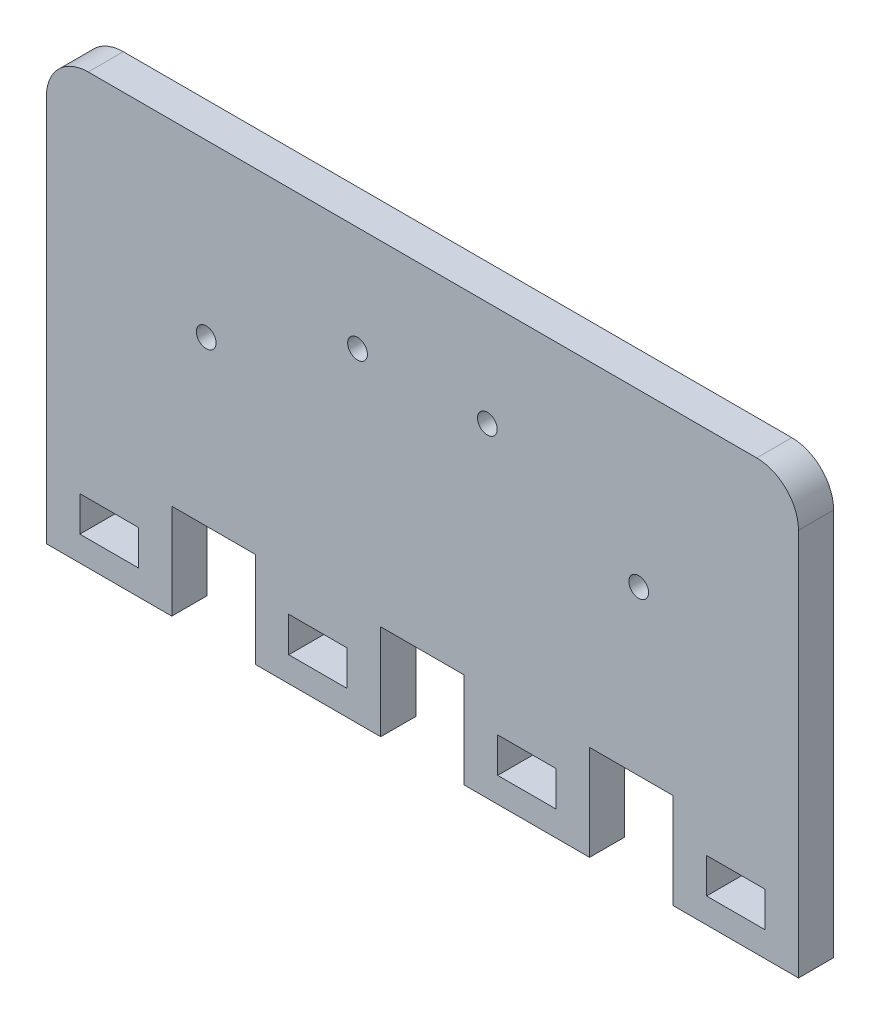
SolidWorks part; units mm, degrees
material "Teak"
ref_plane "Front Plane" through (0, 0, 0) normal (0, 0, 1) x (1, 0, 0)
ref_plane "Top Plane" through (0, 0, 0) normal (0, 1, 0) x (1, 0, 0)
ref_plane "Right Plane" through (0, 0, 0) normal (1, 0, 0) x (0, 0, -1)
sketch "Sketch1" plane through (0, 0, 0) normal (0, 0, 1) x (1, 0, 0)
  line L1 (-30.5325, 25.3111) -> (83.7675, 25.3111)
  line L2 (-30.5325, 25.3111) -> (-30.5325, -30.8229)
  line L3 (-30.5325, -30.8229) -> (83.7675, -30.8229)
  line L4 (83.7675, 25.3111) -> (83.7675, -30.8229)
  dimension "D1" = 56.134
  dimension "D2" = 114.3
extrude "Boss-Extrude1" add sketch "Sketch1" along normal blind 5.334 contours L1 L4 L3 L2
sketch "Sketch2" plane through (0, 0, 5.334) normal (0, 0, 1) x (1, 0, 0)
  line L0 (-30.5325, -30.8229) -> (83.7675, -30.8229) construction
  line L1 (-11.4825, -30.8229) -> (1.2175, -30.8229)
  line L2 (-11.4825, -30.8229) -> (-11.4825, -25.4889)
  line L3 (-11.4825, -25.4889) -> (1.2175, -25.4889)
  line L4 (1.2175, -30.8229) -> (1.2175, -25.4889)
  line L5 (-11.4825, -25.4889) -> (-30.5325, -25.4889) construction
  line L6 (20.2675, -30.8229) -> (32.9675, -30.8229)
  line L7 (20.2675, -30.8229) -> (20.2675, -25.4889)
  line L8 (20.2675, -25.4889) -> (32.9675, -25.4889)
  line L9 (32.9675, -30.8229) -> (32.9675, -25.4889)
  line L10 (52.0175, -30.8229) -> (64.7175, -30.8229)
  line L11 (52.0175, -30.8229) -> (52.0175, -25.4889)
  line L12 (52.0175, -25.4889) -> (64.7175, -25.4889)
  line L13 (64.7175, -30.8229) -> (64.7175, -25.4889)
  line L14 (-30.5325, 25.3111) -> (-30.5325, -30.8229) construction
  line L15 (1.2175, -25.4889) -> (20.2675, -25.4889) construction
  line L16 (32.9675, -25.4889) -> (52.0175, -25.4889) construction
  line L17 (64.7175, -25.4889) -> (83.7675, -25.4889) construction
  line L18 (83.7675, 25.3111) -> (83.7675, -30.8229) construction
  dimension "D1" = 19.05
  dimension "D2" = 12.7
  dimension "D3" = 19.05
  dimension "D4" = 12.7
  dimension "D5" = 19.05
  dimension "D6" = 12.7
  dimension "D7" = 19.05
  dimension "D8" = 5.334
extrude "Cut-Extrude1" cut sketch "Sketch2" against normal through all
fillet "Fillet1" radius 6.35 2 edges at (83.7675, 25.3111, 2.667) (-30.5325, 25.3111, 2.667)
sketch "Sketch3" plane through (0, 0, 0) normal (0, 0, -1) x (-1, 0, 0)
  line L16 (24.1825, 25.3111) -> (-77.4175, 25.3111)
  line L17 (-83.7675, 18.9611) -> (-83.7675, -30.8229)
  line L18 (-83.7675, -30.8229) -> (-64.7175, -30.8229)
  line L19 (-64.7175, -30.8229) -> (-64.7175, -25.4889)
  line L20 (-64.7175, -25.4889) -> (-52.0175, -25.4889)
  line L21 (-52.0175, -25.4889) -> (-52.0175, -30.8229)
  line L22 (-52.0175, -30.8229) -> (-32.9675, -30.8229)
  line L23 (-32.9675, -30.8229) -> (-32.9675, -25.4889)
  line L24 (-32.9675, -25.4889) -> (-20.2675, -25.4889)
  line L25 (-20.2675, -25.4889) -> (-20.2675, -30.8229)
  line L26 (-20.2675, -30.8229) -> (-1.2175, -30.8229)
  line L27 (-1.2175, -30.8229) -> (-1.2175, -25.4889)
  line L28 (-1.2175, -25.4889) -> (11.4825, -25.4889)
  line L29 (11.4825, -25.4889) -> (11.4825, -30.8229)
  line L30 (11.4825, -30.8229) -> (30.5325, -30.8229)
  line L31 (30.5325, -30.8229) -> (30.5325, 18.9611)
  line L32 (24.1825, 25.3111) -> (-77.4175, 25.3111)
  line L33 (-83.7675, 18.9611) -> (-83.7675, -30.8229)
  line L34 (-83.7675, -30.8229) -> (-64.7175, -30.8229)
  line L35 (-64.7175, -30.8229) -> (-64.7175, -25.4889)
  line L36 (-64.7175, -25.4889) -> (-52.0175, -25.4889)
  line L37 (-52.0175, -25.4889) -> (-52.0175, -30.8229)
  line L38 (-52.0175, -30.8229) -> (-32.9675, -30.8229)
  line L39 (-32.9675, -30.8229) -> (-32.9675, -25.4889)
  line L40 (-32.9675, -25.4889) -> (-20.2675, -25.4889)
  line L41 (-20.2675, -25.4889) -> (-20.2675, -30.8229)
  line L42 (-20.2675, -30.8229) -> (-1.2175, -30.8229)
  line L43 (-1.2175, -30.8229) -> (-1.2175, -25.4889)
  line L44 (-1.2175, -25.4889) -> (11.4825, -25.4889)
  line L45 (11.4825, -25.4889) -> (11.4825, -30.8229)
  line L46 (11.4825, -30.8229) -> (30.5325, -30.8229)
  line L47 (30.5325, -30.8229) -> (30.5325, 18.9611)
  line L48 (-83.7675, 18.9611) -> (-83.7675, -30.8229)
  line L49 (24.1825, 25.3111) -> (-77.4175, 25.3111)
  line L50 (30.5325, -30.8229) -> (30.5325, 18.9611)
  line L51 (11.4825, -30.8229) -> (30.5325, -30.8229)
  line L52 (11.4825, -25.4889) -> (11.4825, -30.8229)
  line L53 (-1.2175, -25.4889) -> (11.4825, -25.4889)
  line L54 (-1.2175, -30.8229) -> (-1.2175, -25.4889)
  line L55 (-20.2675, -30.8229) -> (-1.2175, -30.8229)
  line L56 (-20.2675, -25.4889) -> (-20.2675, -30.8229)
  line L57 (-32.9675, -25.4889) -> (-20.2675, -25.4889)
  line L58 (-32.9675, -30.8229) -> (-32.9675, -25.4889)
  line L59 (-52.0175, -30.8229) -> (-32.9675, -30.8229)
  line L60 (-52.0175, -25.4889) -> (-52.0175, -30.8229)
  line L61 (-64.7175, -25.4889) -> (-52.0175, -25.4889)
  line L62 (-64.7175, -30.8229) -> (-64.7175, -25.4889)
  line L63 (-83.7675, -30.8229) -> (-64.7175, -30.8229)
  line L64 (-83.7675, 18.9611) -> (-83.7675, -30.8229)
  line L65 (24.1825, 25.3111) -> (-77.4175, 25.3111)
  line L66 (30.5325, -30.8229) -> (30.5325, 18.9611)
  line L67 (11.4825, -30.8229) -> (30.5325, -30.8229)
  line L68 (11.4825, -25.4889) -> (11.4825, -30.8229)
  line L69 (-1.2175, -25.4889) -> (11.4825, -25.4889)
  line L70 (-1.2175, -30.8229) -> (-1.2175, -25.4889)
  line L71 (-20.2675, -30.8229) -> (-1.2175, -30.8229)
  line L72 (-20.2675, -25.4889) -> (-20.2675, -30.8229)
  line L73 (-32.9675, -25.4889) -> (-20.2675, -25.4889)
  line L74 (-32.9675, -30.8229) -> (-32.9675, -25.4889)
  line L75 (-52.0175, -30.8229) -> (-32.9675, -30.8229)
  line L76 (-52.0175, -25.4889) -> (-52.0175, -30.8229)
  line L77 (-64.7175, -25.4889) -> (-52.0175, -25.4889)
  line L78 (-64.7175, -30.8229) -> (-64.7175, -25.4889)
  line L79 (-83.7675, -30.8229) -> (-64.7175, -30.8229)
  circle A0 centre (6.2485, -0.6449) radius 1.5 construction
  circle A1 centre (-16.7515, 9.3551) radius 1.5 construction
  arc A2 (-77.4175, 25.3111) -> (-83.7675, 18.9611) centre (-77.4175, 18.9611) ccw
  arc A3 (30.5325, 18.9611) -> (24.1825, 25.3111) centre (24.1825, 18.9611) ccw
  arc A4 (-77.4175, 25.3111) -> (-83.7675, 18.9611) centre (-77.4175, 18.9611) ccw
  arc A5 (30.5325, 18.9611) -> (24.1825, 25.3111) centre (24.1825, 18.9611) ccw
  arc A6 (-77.4175, 25.3111) -> (-83.7675, 18.9611) centre (-77.4175, 18.9611) ccw
  arc A7 (30.5325, 18.9611) -> (24.1825, 25.3111) centre (24.1825, 18.9611) ccw
  arc A8 (-77.4175, 25.3111) -> (-83.7675, 18.9611) centre (-77.4175, 18.9611) ccw
  arc A9 (30.5325, 18.9611) -> (24.1825, 25.3111) centre (24.1825, 18.9611) ccw
  circle A10 centre (-59.4835, -0.6449) radius 1.5 construction
  circle A11 centre (-36.4835, 9.3551) radius 1.5 construction
  circle A12 centre (6.2485, -0.6449) radius 1.5
  circle A13 centre (-16.7515, 9.3551) radius 1.5
  circle A14 centre (-59.4835, -0.6449) radius 1.5
  circle A15 centre (-36.4835, 9.3551) radius 1.5
  dimension "D1" = 0
  dimension "D2" = 0
extrude "Cut-Extrude2" cut sketch "Sketch3" against normal through all contours A12 | A13 | A14 | A15
sketch "Sketch4" plane through (0, -30.8229, 0) normal (0, -1, 0) x (-1, 0, 0)
  line L0 (-1.2175, -5.334) -> (-20.2675, -5.334)
  line L1 (30.5325, -5.334) -> (11.4825, -5.334)
  line L2 (30.5325, -5.334) -> (30.5325, 0)
  line L3 (30.5325, 0) -> (11.4825, 0)
  line L4 (11.4825, -5.334) -> (11.4825, 0)
  line L5 (-1.2175, 0) -> (-20.2675, 0)
  line L6 (-20.2675, -5.334) -> (-20.2675, 0)
  line L7 (-1.2175, -5.334) -> (-1.2175, 0)
  line L8 (-32.9675, -5.334) -> (-52.0175, -5.334)
  line L9 (-32.9675, 0) -> (-52.0175, 0)
  line L10 (-52.0175, -5.334) -> (-52.0175, 0)
  line L11 (-32.9675, -5.334) -> (-32.9675, 0)
  line L12 (-64.7175, -5.334) -> (-83.7675, -5.334)
  line L13 (-64.7175, 0) -> (-83.7675, 0)
  line L14 (-83.7675, -5.334) -> (-83.7675, 0)
  line L15 (-64.7175, -5.334) -> (-64.7175, 0)
  dimension "D1" = 4
extrude "Boss-Extrude2" add sketch "Sketch4" along normal blind 9.144
sketch "Sketch6" plane through (0, 0, 5.334) normal (0, 0, 1) x (1, 0, 0)
  line L0 (-30.5325, 18.9611) -> (-30.5325, -39.9669) construction
  line L1 (-25.4525, -30.8229) -> (-16.5625, -30.8229)
  line L2 (-25.4525, -30.8229) -> (-25.4525, -36.1569)
  line L3 (-25.4525, -36.1569) -> (-16.5625, -36.1569)
  line L4 (-16.5625, -30.8229) -> (-16.5625, -36.1569)
  line L5 (-11.4825, -25.4889) -> (-11.4825, -39.9669) construction
  line L6 (1.2175, -25.4889) -> (-11.4825, -25.4889) construction
  line L8 (-5.1325, -25.4889) -> (-5.1325, -40.5378) construction
  line L9 (26.6175, -25.4889) -> (26.6175, -46.02) construction
  line L10 (32.9675, -25.4889) -> (20.2675, -25.4889) construction
  line L11 (58.3675, -25.4889) -> (58.3675, -43.8079) construction
  line L12 (64.7175, -25.4889) -> (52.0175, -25.4889) construction
  line L13 (6.2975, -30.8229) -> (6.2975, -36.1569)
  line L14 (15.1875, -36.1569) -> (6.2975, -36.1569)
  line L15 (15.1875, -30.8229) -> (15.1875, -36.1569)
  line L16 (15.1875, -30.8229) -> (6.2975, -30.8229)
  line L17 (38.0475, -30.8229) -> (46.9375, -30.8229)
  line L18 (38.0475, -30.8229) -> (38.0475, -36.1569)
  line L19 (38.0475, -36.1569) -> (46.9375, -36.1569)
  line L20 (46.9375, -30.8229) -> (46.9375, -36.1569)
  line L21 (69.7975, -30.8229) -> (69.7975, -36.1569)
  line L22 (78.6875, -36.1569) -> (69.7975, -36.1569)
  line L23 (78.6875, -30.8229) -> (78.6875, -36.1569)
  line L24 (78.6875, -30.8229) -> (69.7975, -30.8229)
  dimension "D1" = 5.08
  dimension "D2" = 5.08
  dimension "D3" = 5.334
  dimension "D4" = 5.334
extrude "Cut-Extrude3" cut sketch "Sketch6" against normal through all
equation "\"MDF\"= .21in"
equation "\"Foamcore\"= .13in"
equation "\"Gmaterial\"= \"MDF\""
equation "\"D1@Sketch1\"=\"MDF\"+2"
equation "\"D1@Boss-Extrude1\"=\"MDF\""
equation "\"D8@Sketch2\"=\"MDF\""
equation "\"D3@Sketch6\"=\"MDF\""
equation "\"D4@Sketch6\"=\"MDF\""
